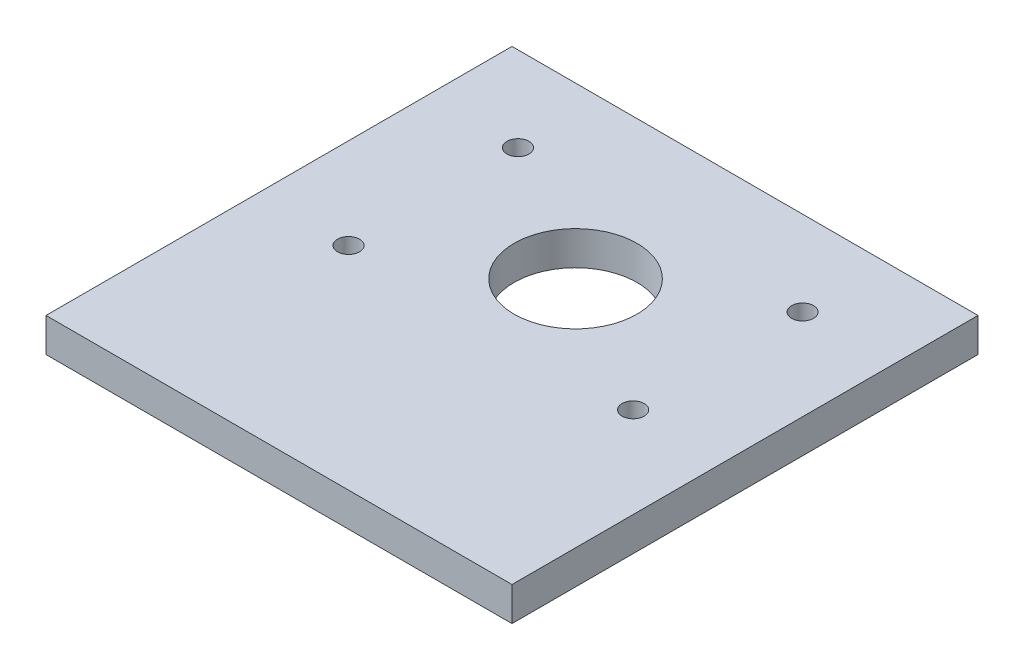
SolidWorks part; units mm, degrees
ref_plane "Front Plane" through (0, 0, 0) normal (0, 0, 1) x (1, 0, 0)
ref_plane "Top Plane" through (0, 0, 0) normal (0, 1, 0) x (1, 0, 0)
ref_plane "Right Plane" through (0, 0, 0) normal (1, 0, 0) x (0, 0, -1)
sketch "Sketch1" plane through (0, 0, 0) normal (0, 1, 0) x (1, 0, 0)
  line L1 (-55, -55) -> (55, -55)
  line L2 (-55, -55) -> (-55, 55)
  line L3 (-55, 55) -> (55, 55)
  line L4 (55, -55) -> (55, 55)
  line L5 (-55, -55) -> (55, 55) construction
  line L6 (-55, 55) -> (55, -55) construction
  line L8 (-33.5915, -5) -> (-33.5915, 35) construction
  line L10 (33.5915, -5) -> (33.5915, 35) construction
  circle A0 centre (0, 15) radius 14.5
  circle A1 centre (-33.5915, 35) radius 2.6
  circle A2 centre (33.5915, 35) radius 2.6
  circle A3 centre (33.5915, -5) radius 2.6
  circle A4 centre (-33.5915, -5) radius 2.6
  point P0 (0, 0)
  point P8 (0, 0)
  point P17 (33.5915, 20)
  point P18 (0, 0)
  dimension "D3" = 29
  dimension "D7" = 5.2
  dimension "D8" = 5.2
  dimension "D9" = 5.2
  dimension "D10" = 5.2
  dimension "D1" = 110
  dimension "D2" = 110
  dimension "D4" = 15
  dimension "D5" = 67.183
  dimension "D6" = 40
  dimension "D11" = 20
extrude "Boss-Extrude1" add sketch "Sketch1" along normal blind 8
